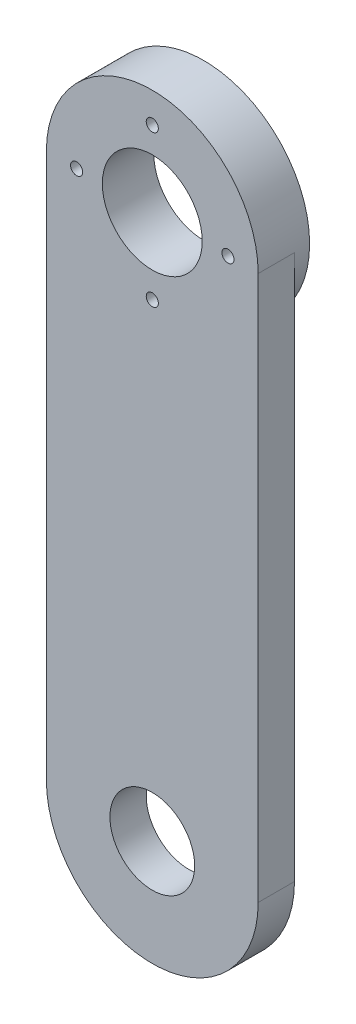
SolidWorks part; units mm, degrees
ref_plane "Front Plane" through (0, 0, 0) normal (0, 0, 1) x (1, 0, 0)
ref_plane "Top Plane" through (0, 0, 0) normal (0, 1, 0) x (1, 0, 0)
ref_plane "Right Plane" through (0, 0, 0) normal (1, 0, 0) x (0, 0, -1)
sketch "Sketch2" plane through (0, 0, 0) normal (0, 0, 1) x (1, 0, 0)
  line L0 (0, 53.1387) -> (0, -126.8613) construction
  line L1 (35, 53.1387) -> (35, -126.8613)
  line L2 (-35, 53.1387) -> (-35, -126.8613)
  arc A0 (35, 53.1387) -> (-35, 53.1387) centre (0, 53.1387) ccw
  arc A1 (-35, -126.8613) -> (35, -126.8613) centre (0, -126.8613) ccw
  circle A2 centre (0, 53.1387) radius 16.5
  circle A3 centre (0, -126.8613) radius 14
  circle A4 centre (0, 53.1387) radius 25 construction
  circle A5 centre (0, 78.1387) radius 2
  circle A6 centre (-25, 53.1387) radius 2
  circle A7 centre (0, 28.1387) radius 2
  circle A8 centre (25, 53.1387) radius 2
  point P3 (0, -36.8613)
  point P8 (0, 88.1387)
  point P9 (0, -161.8613)
  dimension "D3" = 33
  dimension "D4" = 28
  dimension "D5" = 53.1387
  dimension "D6" = 50
  dimension "D7" = 4
  dimension "D8" = 4
  dimension "D9" = 4
  dimension "D10" = 4
  dimension "D1" = 250
  dimension "D2" = 70
extrude "Boss-Extrude1" add sketch "Sketch2" along normal blind 12
sketch "Sketch3" plane through (0, 0, 0) normal (0, 0, -1) x (-1, 0, 0)
  line L2 (-35, 53.1387) -> (-35, -126.8613)
  line L3 (35, -126.8613) -> (35, 53.1387)
  line L4 (-35, 53.1387) -> (-35, -126.8613)
  line L5 (35, -126.8613) -> (35, 53.1387)
  circle A0 centre (0, 53.1387) radius 35
  circle A1 centre (0, 53.1387) radius 16.5 construction
  arc A2 (35, 53.1387) -> (-35, 53.1387) centre (0, 53.1387) ccw
  arc A3 (-35, -126.8613) -> (35, -126.8613) centre (0, -126.8613) ccw
  arc A4 (35, 53.1387) -> (-35, 53.1387) centre (0, 53.1387) ccw
  arc A5 (-35, -126.8613) -> (35, -126.8613) centre (0, -126.8613) ccw
  circle A6 centre (25, 53.1387) radius 2 construction
  circle A7 centre (0, 78.1387) radius 2 construction
  circle A8 centre (-25, 53.1387) radius 2 construction
  circle A9 centre (0, 28.1387) radius 2 construction
  circle A10 centre (0, 53.1387) radius 16.5
  circle A11 centre (25, 53.1387) radius 2
  circle A12 centre (0, 78.1387) radius 2
  circle A13 centre (-25, 53.1387) radius 2
  circle A14 centre (0, 28.1387) radius 2
  arc M5 (35, 53.1387) -> (-35, 53.1387) centre (0, 53.1387) ccw
  circle M9 centre (0, 53.1387) radius 16.5
  circle M11 centre (0, 78.1387) radius 2
  circle M12 centre (25, 53.1387) radius 2
  circle M13 centre (0, 28.1387) radius 2
  circle M14 centre (-25, 53.1387) radius 2
  dimension "D1" = 0
extrude "Boss-Extrude2" add sketch "Sketch3" along normal blind 5 contours A0 M5 M12 M14 M13 M11 M9
